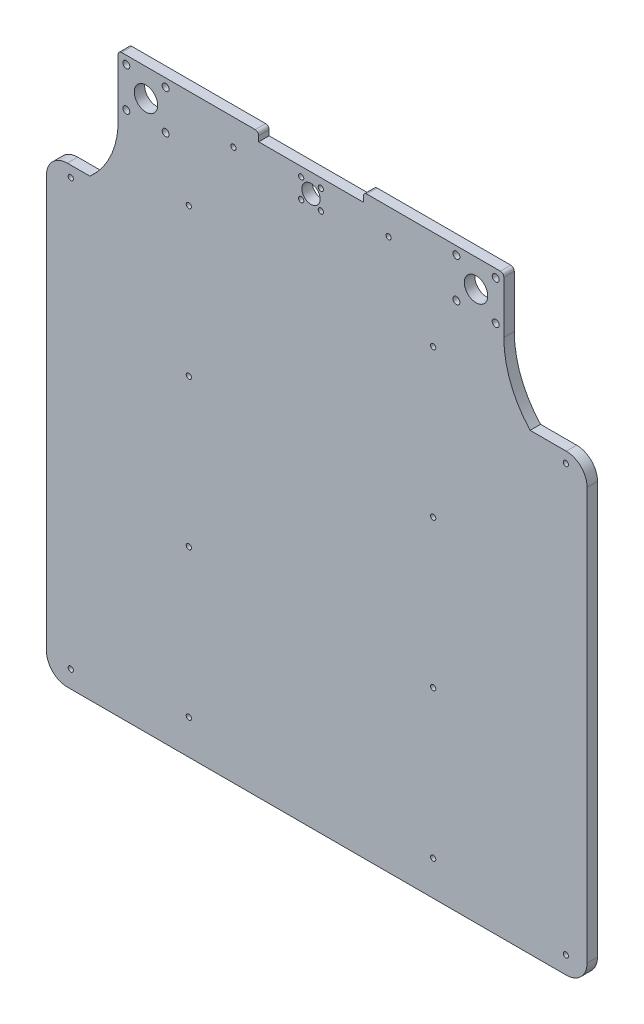
SolidWorks part; units mm, degrees
ref_plane "Alzado" through (0, 0, 0) normal (0, 0, 1) x (1, 0, 0)
ref_plane "Planta" through (0, 0, 0) normal (0, 1, 0) x (1, 0, 0)
ref_plane "Vista lateral" through (0, 0, 0) normal (1, 0, 0) x (0, 0, -1)
sketch "Croquis1" plane through (0, 0, 0) normal (0, 0, 1) x (1, 0, 0)
  line L0 (32.1154, 16) -> (87.6356, 16)
  line L1 (-109, 16) -> (-87.6356, 16)
  line L2 (-111, 14) -> (-111, -16.0875)
  line L3 (-135.2776, -316) -> (-119.3643, -316)
  line L4 (-87.6356, 16) -> (-44.6644, 16)
  line L5 (30.1154, 14) -> (30.1154, 10.91)
  line L6 (0, 0) -> (0, 78.8056) construction
  line L7 (30.1154, 10.91) -> (-30.1154, 10.91)
  line L8 (-111, 0) -> (-111, -16)
  line L9 (-111, -16) -> (-111, 16)
  line L10 (-44.6644, 16) -> (-32.1154, 16)
  line L11 (-119.3643, -316) -> (119.3644, -316)
  line L12 (111, 14) -> (111, -16.0875)
  line L13 (109, 16) -> (87.6356, 16)
  line L14 (-30.1154, 14) -> (-30.1154, 10.91)
  line L15 (-8.3, -8.3) -> (8.3, 8.3) construction
  line L16 (-127.2776, -54.7893) -> (126.134, -54.7893) construction
  line L17 (-96, -316) -> (-44.6644, -316)
  line L18 (119.3644, -316) -> (130.2951, -316)
  line L19 (-8.3, 8.3) -> (8.3, -8.3) construction
  line L20 (-127.2776, -54.7893) -> (-135.2776, -54.7893)
  line L21 (-111, 16) -> (-79, -16) construction
  line L22 (-111, -16) -> (-79, 16) construction
  line L23 (-135.2776, -54.7893) -> (-140.2776, -54.7893)
  line L24 (-138.2776, -61) -> (-136.7776, -61) construction
  line L26 (-135.2776, -316) -> (-140.2776, -316)
  line L27 (-152.2776, -66.7893) -> (-152.2776, -304)
  line L29 (130.2951, -316) -> (146.9429, -316)
  line L30 (158.9429, -70.8585) -> (158.9429, -304)
  line L31 (145.2224, -61) -> (146.7224, -61) construction
  line L32 (126.134, -54.7893) -> (146.9429, -54.7893)
  line L35 (158.9429, -66.7893) -> (158.9429, -70.8585)
  circle A0 centre (0, 0) radius 5.25
  circle A1 centre (-95, 0) radius 6.75
  circle A2 centre (95, 0) radius 6.75
  circle A3 centre (146.7224, -61) radius 1.5
  circle A4 centre (-83.6863, 11.3137) radius 2
  circle A5 centre (-106.3137, 11.3137) radius 2
  circle A6 centre (-83.6863, -11.3137) radius 2
  circle A7 centre (-106.3137, -11.3137) radius 2
  circle A8 centre (106.3137, -11.3137) radius 2
  circle A9 centre (83.6863, -11.3137) radius 2
  circle A10 centre (83.6863, 11.3137) radius 2
  arc A11 (-111, -16.0875) -> (-127.2776, -54.7893) centre (-158.9474, -18.6953) cw
  arc A12 (111, -16.0875) -> (126.134, -54.7893) centre (168.0523, -16.0875) ccw
  arc A13 (-140.2776, -316) -> (-152.2776, -304) centre (-140.2776, -304) cw
  arc A14 (158.9429, -304) -> (146.9429, -316) centre (146.9429, -304) cw
  arc A15 (158.9429, -66.7893) -> (146.9429, -54.7893) centre (146.9429, -66.7893) ccw
  circle A16 centre (5.6569, 5.6569) radius 1.5
  circle A17 centre (-5.6569, 5.6569) radius 1.5
  circle A18 centre (-5.6569, -5.6569) radius 1.5
  circle A19 centre (5.6569, -5.6569) radius 1.5
  arc A20 (-140.2776, -54.7893) -> (-152.2776, -66.7893) centre (-140.2776, -66.7893) ccw
  circle A21 centre (146.7224, -306) radius 1.5
  circle A22 centre (-138.2776, -306) radius 1.5
  circle A23 centre (-138.2776, -61) radius 1.5
  circle A24 centre (-70.3321, -41) radius 1.5
  circle A25 centre (-70.3321, -126) radius 1.5
  circle A26 centre (-70.3321, -211) radius 1.5
  circle A27 centre (-70.3321, -296) radius 1.5
  circle A28 centre (-44.6644, 1) radius 1.5
  arc A29 (109, 16) -> (111, 14) centre (109, 14) cw
  arc A30 (-111, 14) -> (-109, 16) centre (-109, 14) cw
  circle A31 centre (70.3321, -296) radius 1.5
  circle A32 centre (70.3321, -211) radius 1.5
  circle A33 centre (70.3321, -126) radius 1.5
  circle A34 centre (70.3321, -41) radius 1.5
  arc A35 (-32.1154, 16) -> (-30.1154, 14) centre (-32.1154, 14) cw
  circle A36 centre (44.6644, 1) radius 1.5
  circle A37 centre (106.3137, 11.3137) radius 2
  arc A38 (30.1154, 14) -> (32.1154, 16) centre (32.1154, 14) cw
  point P71 (0, 16)
  point P98 (111, 16)
  point P101 (-111, 16)
  point P106 (30.1154, 16)
  point P108 (-147.2776, -54.7893)
  dimension "D3" = 285
  dimension "D4" = 12
  dimension "D5" = 10.5
  dimension "D6" = 14
  dimension "D7" = 285
  dimension "D8" = 13.5
  dimension "D9" = 245
  dimension "D10" = 4
  dimension "D11" = 222
  dimension "D12" = 85
  dimension "D13" = 85
  dimension "D16" = 190
  dimension "D2" = 13.5
  dimension "D18" = 14
  dimension "D21" = 4
  dimension "D19" = 4
  dimension "D20" = 4
  dimension "D22" = 2
  dimension "D24" = 12
  dimension "D25" = 12
  dimension "D14" = 85
  dimension "D15" = 20
  dimension "D17" = 95
  dimension "D23" = 20
  dimension "D26" = 5.2532
  dimension "D27" = 5.2532
  dimension "D28" = 11.3137
  dimension "D29" = 11.3137
  dimension "D30" = 11.3137
  dimension "D31" = 11.3137
extrude "Saliente-Extruir1" add sketch "Croquis1" along normal blind 6
